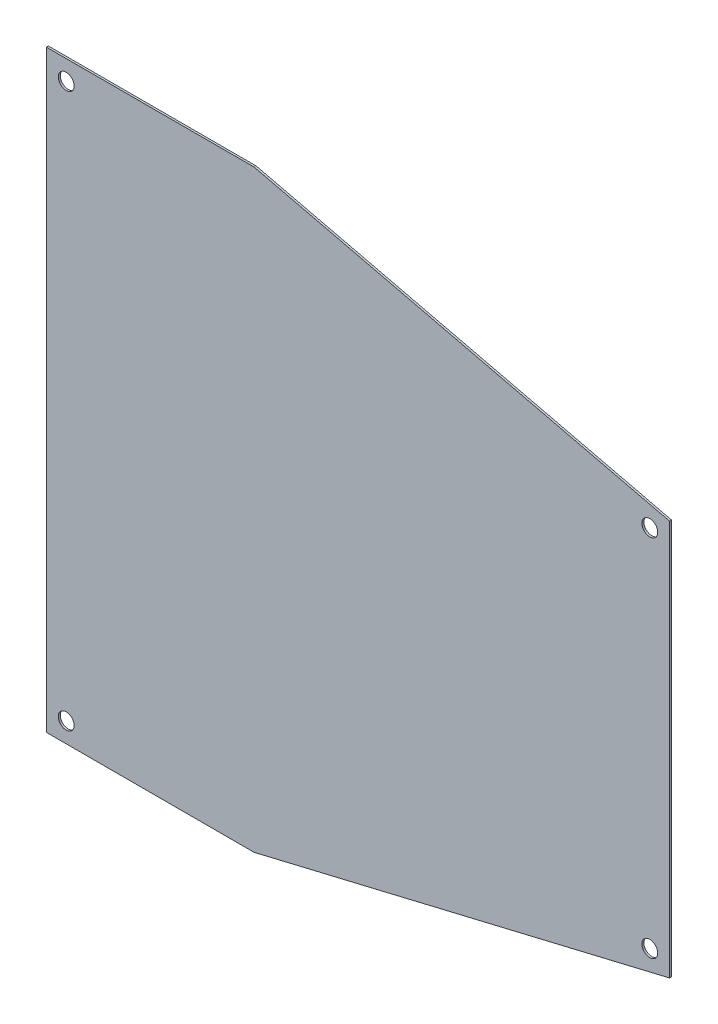
SolidWorks part; units mm, degrees
material "AISI 316 Chapa de aço inoxidável (SS)"
ref_plane "Plano frontal" through (0, 0, 0) normal (0, 0, 1) x (1, 0, 0)
ref_plane "Plano superior" through (0, 0, 0) normal (0, 1, 0) x (1, 0, 0)
ref_plane "Plano direito" through (0, 0, 0) normal (1, 0, 0) x (0, 0, -1)
sketch "Esboço1" plane through (0, 0, 0) normal (0, 0, 1) x (1, 0, 0)
  line L0 (210, 50) -> (105, 75)
  line L1 (52.5, -75) -> (105, -75)
  line L3 (52.5, 75) -> (105, 75)
  line L4 (210, -50) -> (210, 50)
  line L5 (52.5, 75) -> (52.5, -75)
  line L6 (52.5, 0) -> (1090.608, 0) construction
  line L7 (105, -75) -> (210, -50)
  circle A3 centre (57.5, 70) radius 2
  circle A11 centre (205, 46.0507) radius 2
  circle A12 centre (205, -46.0507) radius 2
  circle A13 centre (57.5, -70) radius 2
  point P0 (0, 0)
  dimension "D3" = 5
  dimension "D5" = 5
  dimension "D2" = 4
  dimension "D1" = 25
  dimension "D4" = 5
  dimension "D6" = 5
extrude "Ressalto-extrusão1" add sketch "Esboço1" along normal blind 0.5 contours L6 L5 L1 L7 L4 A12 A13 | L5 L6 L4 L0 L3 A3 A11
